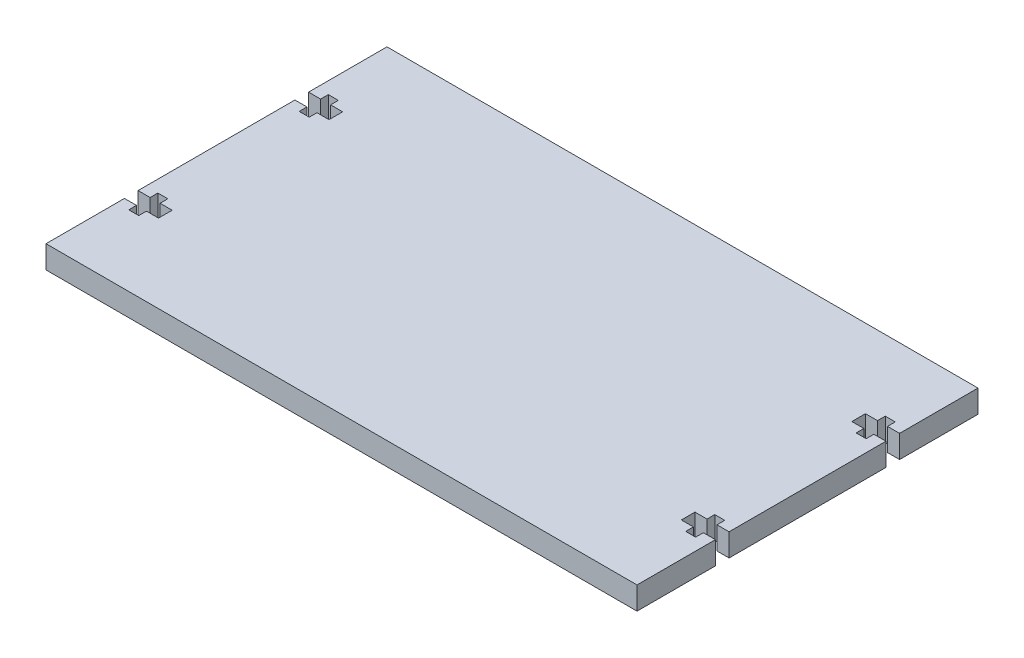
SolidWorks part; units mm, degrees
ref_plane "Front Plane" through (0, 0, 0) normal (0, 0, 1) x (1, 0, 0)
ref_plane "Top Plane" through (0, 0, 0) normal (0, 1, 0) x (1, 0, 0)
ref_plane "Right Plane" through (0, 0, 0) normal (1, 0, 0) x (0, 0, -1)
sketch "Sketch1" plane through (0, 0, 0) normal (0, 1, 0) x (1, 0, 0)
  line L1 (-82.55, -47.625) -> (82.55, -47.625)
  line L2 (-82.55, -47.625) -> (-82.55, 47.625)
  line L3 (-82.55, 47.625) -> (82.55, 47.625)
  line L4 (82.55, -47.625) -> (82.55, 47.625)
  line L5 (-82.55, -47.625) -> (82.55, 47.625) construction
  line L6 (-82.55, 47.625) -> (82.55, -47.625) construction
  point P0 (0, 0)
  dimension "D1" = 165.1
  dimension "D2" = 95.25
extrude "Boss-Extrude1" add sketch "Sketch1" along normal blind 6.35
sketch "Sketch2" plane through (0, 6.35, 0) normal (0, 1, 0) x (1, 0, 0)
  line L0 (-82.55, 0) -> (82.55, 0) construction
  line L1 (82.55, -47.625) -> (82.55, 47.625) construction
  line L2 (82.55, -23.8125) -> (-82.55, -23.8125) construction
  line L3 (-82.55, 47.625) -> (-82.55, -47.625) construction
  line L4 (-82.55, -47.625) -> (82.55, -47.625) construction
  line L5 (82.55, -21.9075) -> (79.1845, -21.9075)
  line L6 (82.55, -25.7175) -> (79.1845, -25.7175)
  line L7 (79.1845, -21.9075) -> (79.1845, -19.7485)
  line L8 (79.1845, -25.7175) -> (79.1845, -27.8765)
  line L9 (79.1845, -19.7485) -> (76.3905, -19.7485)
  line L10 (79.1845, -27.8765) -> (76.3905, -27.8765)
  line L11 (76.3905, -19.7485) -> (76.3905, -21.9075)
  line L12 (76.3905, -27.8765) -> (76.3905, -25.7175)
  line L13 (76.3905, -21.9075) -> (73.025, -21.9075)
  line L14 (76.3905, -25.7175) -> (73.025, -25.7175)
  line L15 (73.025, -21.9075) -> (73.025, -25.7175)
  line L16 (82.55, -21.9075) -> (82.55, -25.7175)
  point P6 (0, 0)
  point P25 (73.025, -23.8125)
  dimension "D1" = 23.8125
  dimension "D2" = 9.525
  dimension "D3" = 3.81
  dimension "D4" = 4.064
  dimension "D5" = 2.794
extrude "Cut-Extrude2" cut sketch "Sketch2" against normal through all
mirror "Mirror1" about plane through (0, 0, 0) normal (0, 0, 1) of "Cut-Extrude2"
mirror "Mirror2" about plane through (0, 0, 0) normal (1, 0, 0) of "Cut-Extrude2", "Mirror1"
